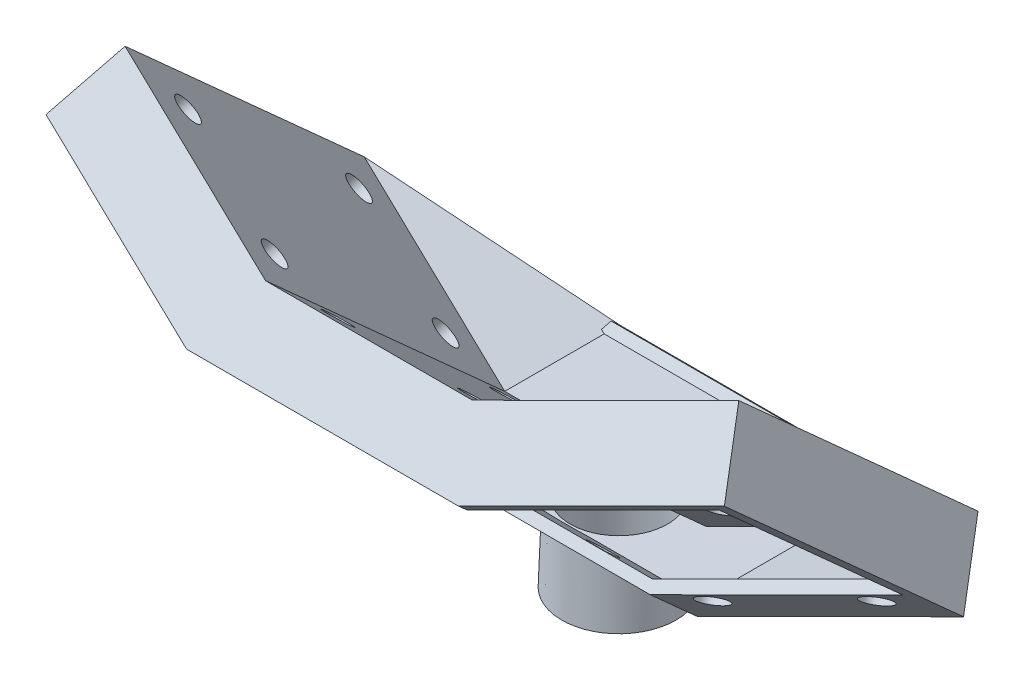
SolidWorks part; units mm, degrees
ref_plane "Front Plane" through (0, 0, 0) normal (0, 0, 1) x (1, 0, 0)
ref_plane "Top Plane" through (0, 0, 0) normal (0, 1, 0) x (1, 0, 0)
ref_plane "Right Plane" through (0, 0, 0) normal (1, 0, 0) x (0, 0, -1)
sketch "Sketch2" plane through (0, 0, 0) normal (0, 1, 0) x (1, 0, 0)
  line L0 (0, 0) -> (30, 0) construction
  dimension "D1" = 30
ref_plane "Plane1" through (0, 0, 0) normal (0, 0.6691, 0.7431) x (1, 0, 0)
sketch "Sketch3" plane through (0, 0, 0) normal (0, 0.6691, 0.7431) x (1, 0, 0)
  line L0 (-9, 0) -> (9, 0)
  line L1 (0, 0) -> (30, 0) construction
  line L2 (9, 0) -> (26.6988, 8.1855)
  line L3 (17.8494, 4.0927) -> (22.0471, -4.9836) construction
  line L4 (0, 0) -> (0, -10) construction
  line L5 (-9, 0) -> (-26.6988, 8.1855)
  line L6 (-17.8494, 4.0927) -> (-22.0471, -4.9836) construction
  line L7 (26.6988, 8.1855) -> (29.5113, 2.1044)
  line L8 (-26.6988, 8.1855) -> (-29.5113, 2.1044)
  line L10 (-29.5113, 2.1044) -> (-11.8125, -6.0811)
  line L12 (-11.8125, -6.0811) -> (11.8125, -6.0811)
  line L13 (11.8125, -6.0811) -> (29.5113, 2.1044)
  point P6 (0, 0)
  point P18 (-26.6988, 8.1855)
  point P21 (26.6988, 8.1855)
  dimension "D1" = 18
  dimension "D2" = 24.82
  dimension "D3" = 19.5
  dimension "D4" = 24.82
  dimension "D5" = 19.5
  dimension "D6" = 10
  dimension "D7" = 10
  dimension "D8" = 10
  dimension "D9" = 6.7
  dimension "D10" = 6.7
  dimension "D11" = 6.7
  dimension "D12" = 6.7
  dimension "D13" = 19.5
  dimension "D14" = 19.5
extrude "Boss-Extrude1" add sketch "Sketch3" along normal blind 28
shell "Shell2" thickness 1
sketch "Sketch5" plane through (0, 0.6691, 0.7431) normal (0, 0.6691, 0.7431) x (1, 0, 0)
  line L0 (-28.6036, 1.6846) -> (-28.1839, 2.5922)
  line L1 (-26.2109, 6.8581) -> (-28.6036, 1.6846) construction
  line L3 (-28.1839, 2.5922) -> (-11.3927, -5.1735)
  line L4 (-28.6036, 1.6846) -> (-11.8125, -6.0811)
  line L5 (28.6036, 1.6846) -> (28.1839, 2.5922)
  line L6 (28.6036, 1.6846) -> (26.2109, 6.8581) construction
  line L8 (-11.8125, -6.0811) -> (11.8125, -6.0811)
  line L9 (-11.3927, -5.1735) -> (11.3927, -5.1735)
  line L10 (28.1839, 2.5922) -> (11.3927, -5.1735)
  line L11 (11.8125, -6.0811) -> (28.6036, 1.6846)
  dimension "D1" = 1
  dimension "D2" = 1
  dimension "D3" = 1
  dimension "D4" = 1
  dimension "D5" = 18.5
  dimension "D6" = 18.5
extrude "Boss-Extrude2" add sketch "Sketch5" along normal blind 4.5
sketch "Sketch6" plane through (0, 0.6691, 0.7431) normal (0, 0.6691, 0.7431) x (1, 0, 0)
  line L0 (9.22, -1) -> (26.2109, 6.8581)
  line L1 (26.2109, 6.8581) -> (28.1839, 2.5922)
  line L2 (28.1839, 2.5922) -> (11.3927, -5.1735)
  line L3 (11.3927, -5.1735) -> (-11.3927, -5.1735)
  line L4 (-11.3927, -5.1735) -> (-28.1839, 2.5922)
  line L5 (-28.1839, 2.5922) -> (-26.2109, 6.8581)
  line L6 (-26.2109, 6.8581) -> (-9.22, -1)
  line L7 (-9.22, -1) -> (9.22, -1)
extrude "Cut-Extrude1" cut sketch "Sketch6" against normal blind 4.5
sketch "Sketch8" plane through (0, 0, 0) normal (0, 0.7431, -0.6691) x (1, 0, 0)
  circle A0 centre (5.93, -3.91) radius 1.2
  circle A1 centre (-5.93, -3.91) radius 1.2
  circle A2 centre (5.93, -23.63) radius 1.2
  circle A3 centre (-5.93, -23.63) radius 1.2
  dimension "D4" = 2.4
  dimension "D7" = 2.4
  dimension "D10" = 2.4
  dimension "D14" = 2.4
  dimension "D2" = 3.91
  dimension "D3" = 5.93
  dimension "D5" = 5.93
  dimension "D6" = 3.91
  dimension "D8" = 5.93
  dimension "D9" = 23.63
  dimension "D11" = 23.63
  dimension "D12" = 5.93
extrude "Cut-Extrude2" cut sketch "Sketch8" against normal blind 24.5
sketch "Sketch9" plane through (1.5859, -2.5482, 2.2944) normal (-0.4198, 0.6745, -0.6073) x (0.9076, 0.3119, -0.2809)
  line L7 (27.6687, 0) -> (8.1687, 0) construction
  line L8 (27.6687, -28) -> (27.6687, 0) construction
  line L9 (8.1687, -28) -> (8.1687, 0) construction
  line L10 (27.6687, -28) -> (8.1687, -28) construction
  circle A0 centre (23.7587, -3.91) radius 1.2
  circle A1 centre (11.7387, -3.91) radius 1.2
  circle A2 centre (23.7587, -23.97) radius 1.2
  circle A3 centre (11.7387, -23.97) radius 1.2
  dimension "D6" = 2.4
  dimension "D9" = 4.03
  dimension "D10" = 2.4
  dimension "D12" = 2.4
  dimension "D16" = 2.4
  dimension "D2" = 3.91
  dimension "D3" = 3.91
  dimension "D4" = 3.91
  dimension "D5" = 3.57
  dimension "D7" = 3.91
  dimension "D8" = 4.03
  dimension "D11" = 3.57
extrude "Cut-Extrude3" cut sketch "Sketch9" against normal blind 24.5
sketch "Sketch10" plane through (-1.5859, -2.5482, 2.2944) normal (0.4198, 0.6745, -0.6073) x (0.9076, -0.3119, 0.2809)
  line L6 (-8.1687, 0) -> (-27.6687, 0) construction
  line L7 (-8.1687, -28) -> (-8.1687, 0) construction
  line L8 (-8.1687, -28) -> (-27.6687, -28) construction
  line L9 (-27.6687, -28) -> (-27.6687, 0) construction
  circle A0 centre (-11.7387, -3.91) radius 1.2
  circle A1 centre (-23.7587, -3.91) radius 1.2
  circle A2 centre (-11.7387, -23.93) radius 1.2
  circle A3 centre (-23.7587, -23.93) radius 1.2
  dimension "D5" = 2.4
  dimension "D6" = 2.4
  dimension "D7" = 2.4
  dimension "D8" = 2.4
  dimension "D1" = 3.91
  dimension "D2" = 3.57
  dimension "D3" = 3.57
  dimension "D4" = 4.07
  dimension "D9" = 4.07
  dimension "D10" = 3.91
  dimension "D11" = 3.91
  dimension "D12" = 3.91
extrude "Cut-Extrude4" cut sketch "Sketch10" against normal blind 24.5
sketch "Sketch11" plane through (0, 0, 0) normal (0, -0.6691, -0.7431) x (-1, 0, 0)
  line L0 (-11.8125, -6.0811) -> (-11.3927, -5.1735)
  line L1 (-11.3927, -5.1735) -> (11.3927, -5.1735)
  line L2 (11.3927, -5.1735) -> (11.8125, -6.0811)
  line L3 (11.8125, -6.0811) -> (-11.8125, -6.0811)
  line L4 (-9.22, -1) -> (-9, 0)
  line L5 (-9, 0) -> (9, 0)
  line L6 (9, 0) -> (9.22, -1)
  line L7 (9.22, -1) -> (-9.22, -1)
extrude "Boss-Extrude3" add sketch "Sketch11" along direction (0, 0, 1) on the side of the normal blind 10
sketch "Sketch12" plane through (0, 0, 0) normal (0, -0.6691, -0.7431) x (-1, 0, 0)
  line L0 (-11.8125, -6.0811) -> (-11.3927, -5.1735)
  line L1 (-11.3927, -5.1735) -> (-28.1839, 2.5922)
  line L2 (-28.1839, 2.5922) -> (-26.2109, 6.8581)
  line L3 (-26.2109, 6.8581) -> (-9.22, -1)
  line L4 (-9.22, -1) -> (-9, 0)
  line L5 (-9, 0) -> (-26.6988, 8.1855)
  line L6 (-26.6988, 8.1855) -> (-29.5113, 2.1044)
  line L7 (-29.5113, 2.1044) -> (-11.8125, -6.0811)
ref_plane "Plane2" through (2.6371, -7.6727, 0) normal (-0.325, 0.9457, 0) x (0.9457, 0.325, 0)
sketch "Sketch13" plane through (2.6371, -7.6727, 0) normal (-0.325, 0.9457, 0) x (0.9457, 0.325, 0)
  line L0 (28.4172, 1.4081) -> (9.7022, 5.9309) construction
extrude "Boss-Extrude4" add sketch "Sketch12" along direction (-0.9192, -0.3159, -0.2349) on the side of the normal up to surface (7.4314 mm away)
sketch "Sketch14" plane through (0, -4.9726, -5.5226) normal (0, -0.6691, -0.7431) x (-1, 0, 0)
  line L0 (4.1487, 0.6102) -> (1.7664, 0.6102)
  line L1 (1.7664, 0.6102) -> (8.4788, -2.4942)
  line L2 (8.4788, -2.4942) -> (8.6988, -1.4942)
  line L3 (8.6988, -1.4942) -> (4.1487, 0.6102)
extrude "Cut-Extrude5" cut sketch "Sketch14" along direction (0, 0, 1) on the side against the normal blind 10
sketch "Sketch15" plane through (0, -4.9726, -5.5226) normal (0, -0.6691, -0.7431) x (-1, 0, 0)
  line L0 (-11.8125, 0.6102) -> (-9.4302, 0.6102)
  line L1 (-9.4302, 0.6102) -> (6.3061, -6.6677)
  line L2 (6.3061, -6.6677) -> (5.8864, -7.5753)
  line L3 (5.8864, -7.5753) -> (-11.8125, 0.6102)
extrude "Cut-Extrude6" cut sketch "Sketch15" along direction (0, 0, 1) on the side against the normal blind 10
sketch "Sketch16" plane through (0, -4.9726, -5.5226) normal (0, -0.6691, -0.7431) x (-1, 0, 0)
  line L0 (-0.196, 1.5178) -> (2.1862, 1.5178)
  line L1 (2.1862, 1.5178) -> (-6.8378, 5.6913)
  line L2 (-6.8378, 5.6913) -> (-8.5121, 5.3639)
  line L3 (-8.5121, 5.3639) -> (-0.196, 1.5178)
extrude "Cut-Extrude7" cut sketch "Sketch16" along direction (0, 0, 1) on the side against the normal blind 10
ref_plane "Plane3" through (-0.9508, -2.7665, 0) normal (0.325, 0.9457, 0) x (0.9457, -0.325, 0)
sketch "Sketch17" plane through (-0.9508, -2.7665, 0) normal (0.325, 0.9457, 0) x (0.9457, -0.325, 0)
  line L0 (-27.2263, 5.4772) -> (-8.5113, 10) construction
sketch "Sketch18" plane through (0, 0, 0) normal (0, -0.6691, -0.7431) x (-1, 0, 0)
  line L0 (9, 0) -> (9.22, -1)
  line L1 (9.22, -1) -> (26.2109, 6.8581)
  line L2 (26.2109, 6.8581) -> (28.1839, 2.5922)
  line L3 (28.1839, 2.5922) -> (11.3927, -5.1735)
  line L4 (11.3927, -5.1735) -> (11.8125, -6.0811)
  line L5 (11.8125, -6.0811) -> (29.5113, 2.1044)
  line L6 (29.5113, 2.1044) -> (26.6988, 8.1855)
  line L7 (26.6988, 8.1855) -> (9, 0)
extrude "Boss-Extrude5" add sketch "Sketch18" along direction (0.9192, -0.3159, -0.2349) on the side of the normal up to surface (7.4314 mm away)
sketch "Sketch19" plane through (0, -4.9726, -5.5226) normal (0, -0.6691, -0.7431) x (-1, 0, 0)
  line L0 (6.8378, 5.6913) -> (8.5121, 5.3639)
  line L1 (8.5121, 5.3639) -> (0.196, 1.5178)
  line L2 (0.196, 1.5178) -> (-2.1862, 1.5178)
  line L3 (-2.1862, 1.5178) -> (6.8378, 5.6913)
  line L4 (-4.1487, 0.6102) -> (-1.7664, 0.6102)
  line L5 (-1.7664, 0.6102) -> (-8.4788, -2.4942)
  line L6 (-8.4788, -2.4942) -> (-8.6988, -1.4942)
  line L7 (-8.6988, -1.4942) -> (-4.1487, 0.6102)
  line L8 (9.4302, 0.6102) -> (11.8125, 0.6102)
  line L9 (11.8125, 0.6102) -> (-5.8864, -7.5753)
  line L10 (-5.8864, -7.5753) -> (-6.3061, -6.6677)
  line L11 (-6.3061, -6.6677) -> (9.4302, 0.6102)
extrude "Cut-Extrude8" cut sketch "Sketch19" along direction (0, 0, 1) on the side against the normal blind 10
sketch "Sketch20" plane through (0, -4.9726, -5.5226) normal (0, -0.6691, -0.7431) x (-1, 0, 0)
  line L0 (-11.8125, 0.6102) -> (-9, 6.6913)
  line L1 (-9, 6.6913) -> (9, 6.6913)
  line L2 (9, 6.6913) -> (11.8125, 0.6102)
  line L3 (11.8125, 0.6102) -> (-11.8125, 0.6102)
extrude "Boss-Extrude6" add sketch "Sketch20" against normal blind 1
sketch "Sketch23" plane through (0, -4.5192, 0) normal (0, -1, 0) x (1, 0, 0)
  line L0 (-11.8125, 4.0691) -> (11.8125, 4.0691) construction
  line L3 (11.8125, 4.0691) -> (11.8125, -5.9309) construction
  circle A0 centre (0.0025, -0.9309) radius 4.75
  dimension "D2" = 9.5
  dimension "D1" = 5
  dimension "D3" = 11.81
extrude "Cut-Extrude9" cut sketch "Sketch23" against normal blind 1
sketch "Sketch24" plane through (0, -4.5192, 0) normal (0, -1, 0) x (1, 0, 0)
  line L0 (-11.8125, 4.0691) -> (11.8125, 4.0691) construction
  line L1 (-11.8125, 4.0691) -> (-11.8125, -5.9309) construction
  circle A0 centre (0.0025, -0.9309) radius 4.755
  dimension "D1" = 9.51
  dimension "D2" = 5
  dimension "D3" = 11.8149
extrude "Boss-Extrude7" add sketch "Sketch24" along normal blind 6.2 draft 2 and the other way up to surface (0.6745 mm away)
sketch "Sketch28" plane through (0, -3.8447, 0) normal (0, 1, 0) x (1, 0, 0)
  line L1 (-11.8125, -4.0691) -> (11.8125, -4.0691) construction
  line L2 (11.8125, -4.0691) -> (11.8125, 5.9309) construction
  circle A0 centre (0.0025, 0.9309) radius 4.245
  dimension "D1" = 8.49
  dimension "D2" = 5
  dimension "D3" = 11.81
extrude "Cut-Extrude10" cut sketch "Sketch28" against normal blind 76 draft 2 draft outward yes
